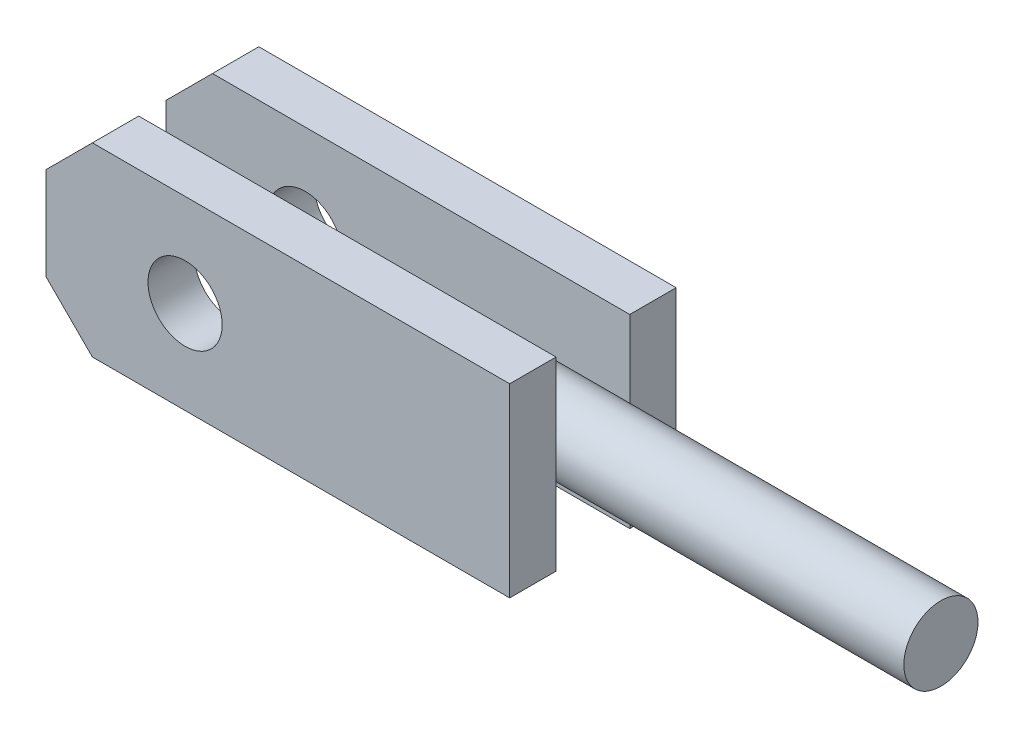
SolidWorks part; units mm, degrees
material "ASTM A36"
ref_plane "Front Plane" through (0, 0, 0) normal (0, 0, 1) x (1, 0, 0)
ref_plane "Top Plane" through (0, 0, 0) normal (0, 1, 0) x (1, 0, 0)
ref_plane "Right Plane" through (0, 0, 0) normal (1, 0, 0) x (0, 0, -1)
sketch "Sketch1" plane through (0, 0, 0) normal (0, 0, 1) x (1, 0, 0)
  line L1 (50, -20) -> (-50, -20)
  line L2 (50, -20) -> (50, 20)
  line L3 (50, 20) -> (-50, 20)
  line L4 (-50, -20) -> (-50, 20)
  line L5 (50, -20) -> (-50, 20) construction
  line L6 (50, 20) -> (-50, -20) construction
  point P0 (0, 0)
  dimension "D1" = 40
  dimension "D2" = 100
extrude "Boss-Extrude1" add sketch "Sketch1" along normal blind 10
sketch "Sketch4" plane through (0, 0, 10) normal (0, 0, 1) x (1, 0, 0)
  line L0 (-50, 20) -> (-50, -20) construction
  circle A0 centre (-20, 0) radius 8
  dimension "D2" = 16
  dimension "D1" = 30
extrude "Cut-Extrude1" cut sketch "Sketch4" against normal blind 10
chamfer "Chamfer2" distance 10 angle 45 1 edges at (-50, 20, 5)
chamfer "Chamfer3" distance 10 angle 45 1 edges at (-50, -20, 5)
sketch "Sketch5" plane through (50, 0, 0) normal (1, 0, 0) x (0, 0, -1)
  line L0 (0, -20) -> (0, 20) construction
  circle A0 centre (8, 0) radius 8
  dimension "D1" = 16
  dimension "D2" = 8
extrude "Boss-Extrude2" add sketch "Sketch5" along normal blind 75 and the other way blind 20 separate body
pattern_linear "LPattern1" count 2 spacing 25.9 along (0, 0, -1) of "Boss-Extrude1"
chamfer "Chamfer4" distance 10 angle 45 1 edges at (-50, 20, -20.9)
chamfer "Chamfer5" distance 10 angle 45 1 edges at (-50, -20, -20.9)
sketch "Sketch6" plane through (0, 0, -25.9) normal (0, 0, -1) x (-1, 0, 0)
  line L0 (50, 10) -> (50, -10) construction
  circle A0 centre (20, 0) radius 8
  dimension "D1" = 30
  dimension "D2" = 16
extrude "Cut-Extrude2" cut sketch "Sketch6" against normal blind 100
